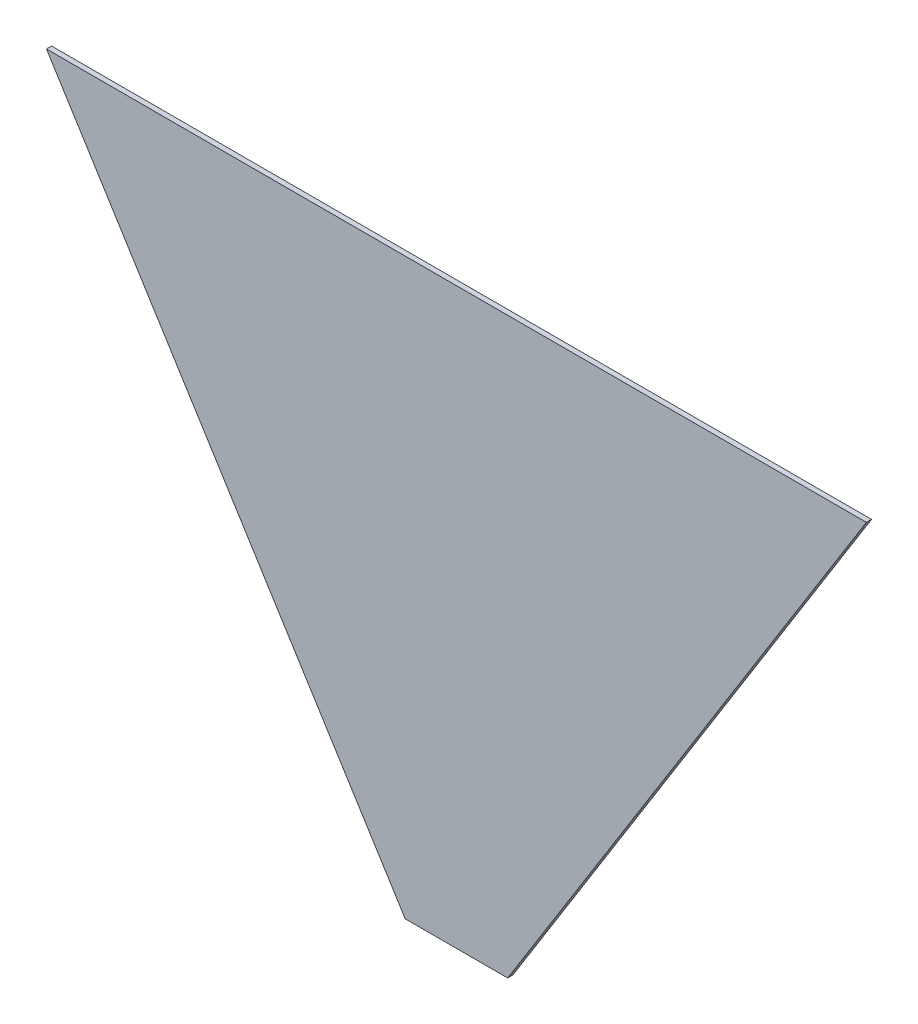
SolidWorks part; units mm, degrees
ref_plane "Front Plane" through (0, 0, 0) normal (0, 0, 1) x (1, 0, 0)
ref_plane "Top Plane" through (0, 0, 0) normal (0, 1, 0) x (1, 0, 0)
ref_plane "Right Plane" through (0, 0, 0) normal (1, 0, 0) x (0, 0, -1)
sketch "Sketch1" plane through (0, 0, 0) normal (0, 0, 1) x (1, 0, 0)
  line L1 (127, -88.9) -> (-127, -88.9)
  line L2 (127, -88.9) -> (127, 88.9)
  line L3 (127, 88.9) -> (-127, 88.9)
  line L4 (-127, -88.9) -> (-127, 88.9)
  line L5 (127, -88.9) -> (-127, 88.9) construction
  line L6 (127, 88.9) -> (-127, -88.9) construction
  point P0 (0, 0)
  dimension "D1" = 254
  dimension "D2" = 177.8
extrude "Boss-Extrude1" add sketch "Sketch1" along normal blind 1.5875
sketch "Sketch2" plane through (0, 0, 1.5875) normal (0, 0, 1) x (1, 0, 0)
  line L0 (0, 88.9) -> (0, -88.9) construction
  line L1 (127, 88.9) -> (-127, 88.9) construction
  line L2 (-127, -88.9) -> (127, -88.9) construction
  line L3 (127, 88.9) -> (15.875, -88.9)
  line L4 (-127, 88.9) -> (-15.875, -88.9)
  line L9 (-127, 88.9) -> (-127, -88.9)
  line L10 (-127, -88.9) -> (127, -88.9)
  line L11 (127, -88.9) -> (127, 88.9)
  line L12 (127, 88.9) -> (-127, 88.9)
  line L13 (-127, 88.9) -> (-127, -88.9)
  line L14 (-127, -88.9) -> (127, -88.9)
  line L15 (127, -88.9) -> (127, 88.9)
  line M6 (-127, 88.9) -> (-127, -88.9)
  line M7 (-127, -88.9) -> (127, -88.9)
  line M8 (127, -88.9) -> (127, 88.9)
  dimension "D1" = 15.875
  dimension "D2" = 15.875
  dimension "D3" = 0
extrude "Cut-Extrude1" cut sketch "Sketch2" against normal up to next contours L3 M8 M7 | L4 M6 M7
